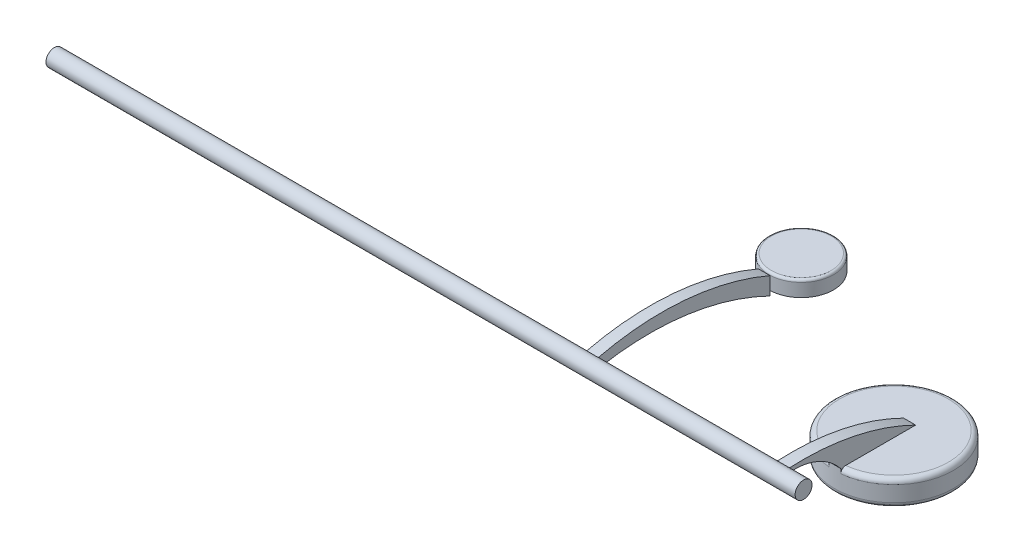
SolidWorks part; units mm, degrees
material "6061 Alloy"
ref_plane "Front Plane" through (0, 0, 0) normal (0, 0, 1) x (1, 0, 0)
ref_plane "Top Plane" through (0, 0, 0) normal (0, 1, 0) x (1, 0, 0)
ref_plane "Right Plane" through (0, 0, 0) normal (1, 0, 0) x (0, 0, -1)
sketch "Sketch1" plane through (0, 0, 0) normal (1, 0, 0) x (0, 0, -1)
  circle A0 centre (0, 0) radius 2.2225
  dimension "D1" = 4.445
extrude "Boss-Extrude1" add sketch "Sketch1" along normal blind 196.85
ref_plane "Plane1" through (191.3128, 0, 0) normal (1, 0, 0) x (0, 0, -1)
sketch "Sketch2" plane through (191.3128, 0, 0) normal (1, 0, 0) x (0, 0, -1)
  line L0 (15.24, -5.5372) -> (34.9758, -5.5372)
  line L1 (2.4447, 0) -> (-2.4447, 0) construction
  line L2 (0, 2.4447) -> (0, -2.4447) construction
  line L3 (0, 0) -> (0, 1.1757)
  arc A0 (0, 0) -> (15.24, -5.5372) centre (3.12, -15.154) cw
  arc A1 (0, 1.1757) -> (34.9758, -5.5372) centre (5.3349, -65.5014) cw
  point P11 (0, 0)
  point P12 (0, 0)
  dimension "D4" = 15.4719
  dimension "D5" = 66.8901
  dimension "D1" = 5.5372
  dimension "D2" = 19.7358
  dimension "D3" = 15.24
extrude "Boss-Extrude2" add sketch "Sketch2" against normal blind 3.175
sketch "Sketch3" plane through (0, -5.5372, 0) normal (0, -1, 0) x (1, 0, 0)
  line L0 (189.7253, -15.24) -> (189.7253, -34.9758) construction
  line L1 (188.1378, -15.24) -> (191.3128, -15.24) construction
  line L2 (188.1378, -34.9758) -> (191.3128, -34.9758) construction
  circle A0 centre (189.7253, -30.861) radius 15.621
  dimension "D1" = 31.242
extrude "Boss-Extrude3" add sketch "Sketch3" along normal blind 6.6548
fillet "Fillet1" radius 1.27 2 edges at (189.7253, -5.5372, -46.482) (189.7253, -12.192, -46.482)
ref_plane "Plane2" through (141.5542, 0, 0) normal (-1, 0, 0) x (0, 0, 1)
sketch "Sketch6" plane through (141.5542, 0, 0) normal (-1, 0, 0) x (0, 0, 1)
  line L0 (-46.482, -6.8072) -> (-46.482, -2.159)
  line L1 (0, -1.0365) -> (0, 1.4305)
  arc A0 (0, -1.0365) -> (-46.482, -6.8072) centre (-14.8798, -71.2694) ccw
  arc A1 (0, 1.4305) -> (-46.482, -2.159) centre (-17.9955, -68.2906) ccw
  dimension "D1" = 4.6482
  dimension "D2" = 72.006
  dimension "D3" = 71.7919
extrude "Boss-Extrude4" add sketch "Sketch6" along normal blind 3.048
ref_plane "Plane3" through (140.0302, 0, 0) normal (-1, 0, 0) x (0, 0, 1)
sketch "Sketch7" plane through (140.0302, 0, 0) normal (-1, 0, 0) x (0, 0, 1)
  line L1 (-47.7256, -6.8072) -> (-56.2092, -6.8072)
  line L2 (-47.7256, -6.8072) -> (-47.7256, -2.7087)
  line L3 (-47.7256, -2.7087) -> (-56.2092, -2.7087)
  line L4 (-56.2092, -6.8072) -> (-56.2092, -2.7087)
  arc A0 (-1.3505, 1.7652) -> (-46.482, -2.159) centre (-17.9955, -68.2906) ccw construction
  point P4 (0, 0)
  point P5 (0, 0)
  point P9 (-52.2055, -3.1168)
  point P10 (-47.7256, -1.9138)
  dimension "D1" = 8.4836
revolve "Revolve1" add sketch "Sketch7" angle 360 about L4
fillet "Fillet3" radius 0.635 1 edges at (140.0302, -2.7087, -64.6928)
